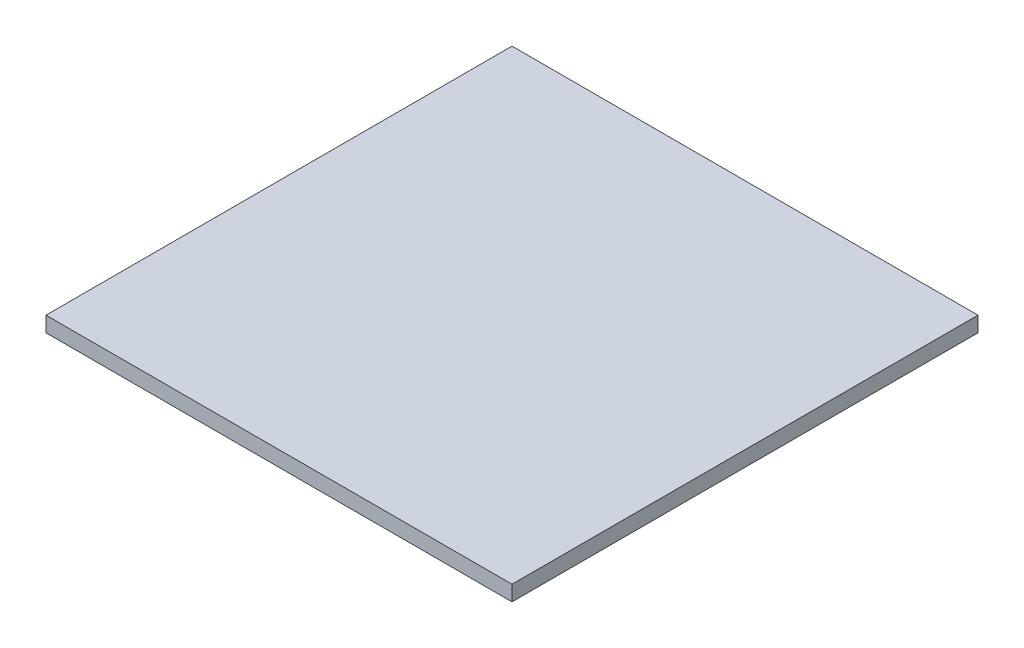
SolidWorks part; units mm, degrees
ref_plane "Front Plane" through (0, 0, 0) normal (0, 0, 1) x (1, 0, 0)
ref_plane "Top Plane" through (0, 0, 0) normal (0, 1, 0) x (1, 0, 0)
ref_plane "Right Plane" through (0, 0, 0) normal (1, 0, 0) x (0, 0, -1)
sketch "Sketch1" plane through (0, 0, 0) normal (0, 1, 0) x (1, 0, 0)
  line L1 (-152.4, -152.4) -> (152.4, -152.4)
  line L2 (-152.4, -152.4) -> (-152.4, 152.4)
  line L3 (-152.4, 152.4) -> (152.4, 152.4)
  line L4 (152.4, -152.4) -> (152.4, 152.4)
  line L5 (-152.4, -152.4) -> (152.4, 152.4) construction
  line L6 (-152.4, 152.4) -> (152.4, -152.4) construction
  point P0 (0, 0)
  dimension "D1" = 304.8
extrude "Boss-Extrude1" add sketch "Sketch1" along normal blind 10
